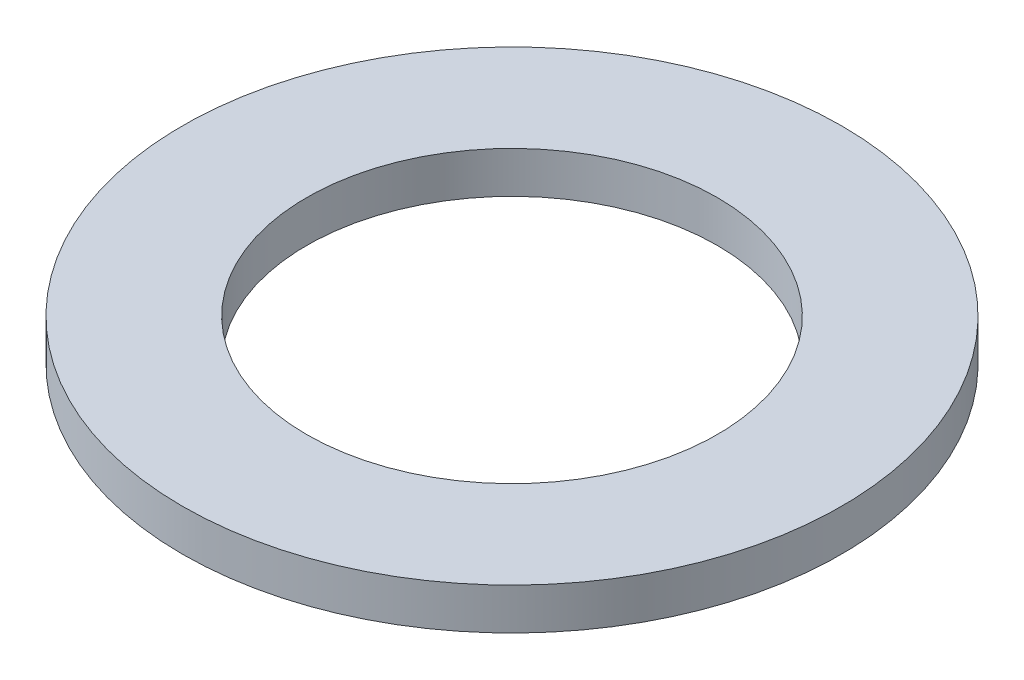
SolidWorks part; units mm, degrees
ref_plane "Front Plane" through (0, 0, 0) normal (0, 0, 1) x (1, 0, 0)
ref_plane "Top Plane" through (0, 0, 0) normal (0, 1, 0) x (1, 0, 0)
ref_plane "Right Plane" through (0, 0, 0) normal (1, 0, 0) x (0, 0, -1)
sketch "Sketch1" plane through (0, 0, 0) normal (0, 1, 0) x (1, 0, 0)
  circle A0 centre (0, 0) radius 7.9121
  circle A1 centre (0, 0) radius 12.7
  dimension "D1" = 15.8242
  dimension "D2" = 25.4
extrude "Boss-Extrude1" add sketch "Sketch1" along normal blind 1.6
